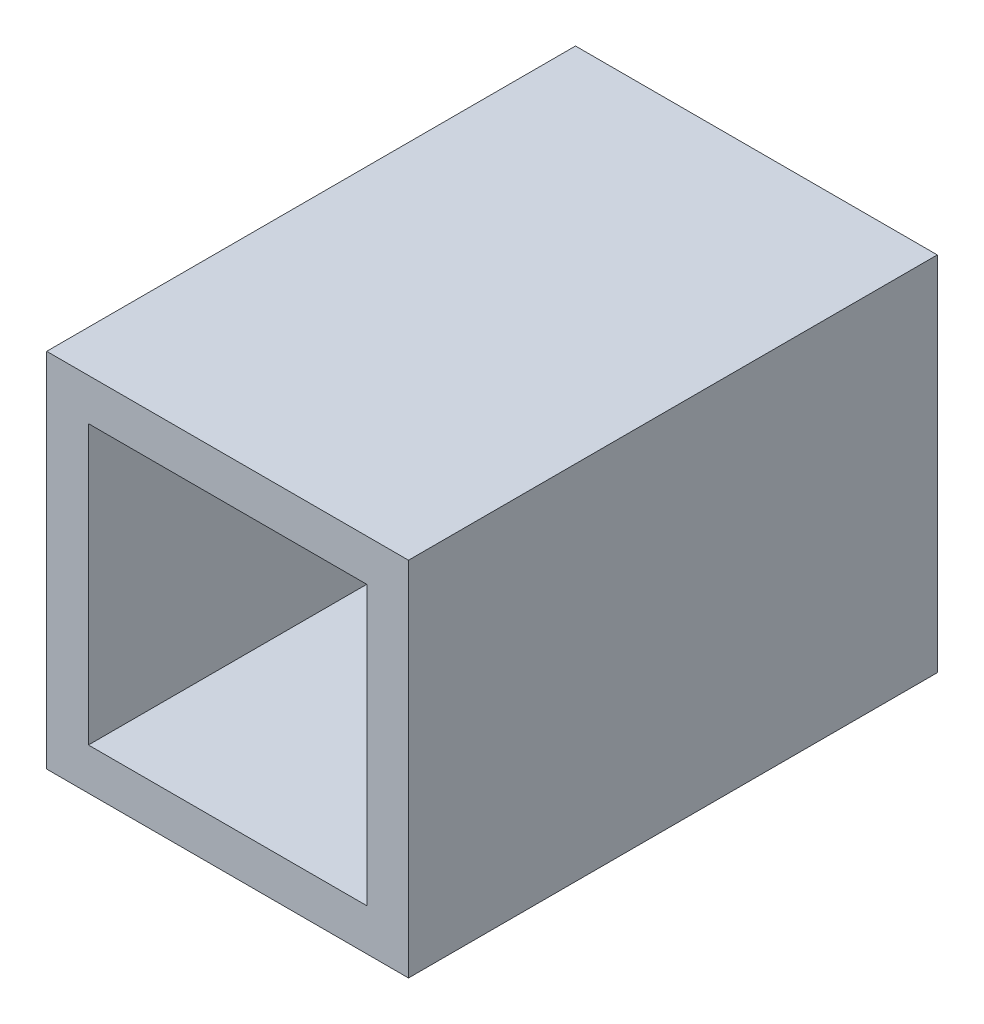
SolidWorks part; units mm, degrees
ref_plane "Front Plane" through (0, 0, 0) normal (0, 0, 1) x (1, 0, 0)
ref_plane "Top Plane" through (0, 0, 0) normal (0, 1, 0) x (1, 0, 0)
ref_plane "Right Plane" through (0, 0, 0) normal (1, 0, 0) x (0, 0, -1)
sketch "Sketch1" plane through (0, 0, 0) normal (0, 0, 1) x (1, 0, 0)
  line L1 (-6.5, 6.5) -> (6.5, 6.5)
  line L2 (-6.5, 6.5) -> (-6.5, -6.5)
  line L3 (-6.5, -6.5) -> (6.5, -6.5)
  line L4 (6.5, 6.5) -> (6.5, -6.5)
  line L5 (-6.5, 6.5) -> (6.5, -6.5) construction
  line L6 (-6.5, -6.5) -> (6.5, 6.5) construction
  line L7 (-5, -5) -> (5, -5)
  line L8 (-5, -5) -> (-5, 5)
  line L9 (-5, 5) -> (5, 5)
  line L10 (5, -5) -> (5, 5)
  line L11 (-5, -5) -> (5, 5) construction
  line L12 (-5, 5) -> (5, -5) construction
  point P0 (0, 0)
  point P6 (0, 0)
  dimension "D1" = 13
  dimension "D2" = 13
  dimension "D3" = 1.5
extrude "Boss-Extrude1" add sketch "Sketch1" along normal blind 19
